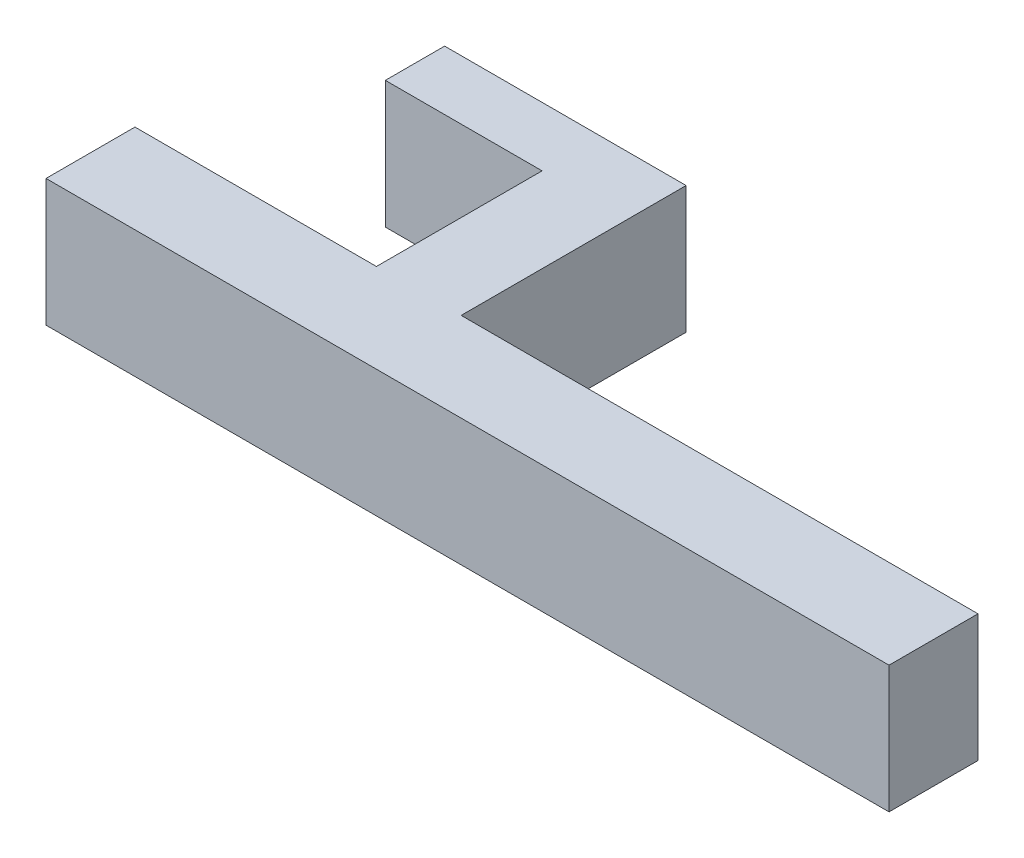
SolidWorks part; units mm, degrees
ref_plane "Plano frontal" through (0, 0, 0) normal (0, 0, 1) x (1, 0, 0)
ref_plane "Plano superior" through (0, 0, 0) normal (0, 1, 0) x (1, 0, 0)
ref_plane "Plano direito" through (0, 0, 0) normal (1, 0, 0) x (0, 0, -1)
sketch "Esboço1" plane through (0, 0, 0) normal (0, 1, 0) x (1, 0, 0)
  line L0 (0, 0) -> (19.9, 0)
  line L1 (19.9, 0) -> (19.9, 2.5)
  line L2 (19.9, 2.5) -> (7.7, 2.5)
  line L3 (7.7, 2.5) -> (7.7, 7.91)
  line L4 (7.7, 7.91) -> (2, 7.91)
  line L5 (2, 7.91) -> (2, 5.91)
  line L6 (2, 5.91) -> (5.7, 5.91)
  line L7 (5.7, 5.91) -> (5.7, 2.5)
  line L8 (5.7, 2.5) -> (0, 2.5)
  line L9 (0, 2.5) -> (0, 0)
  line L10 (2.1037, 2.5) -> (2.1037, 5.91) construction
  line L12 (2, 7.61) -> (7.7, 7.61)
  line L13 (2, 6.21) -> (5.7, 6.21)
  line L14 (5.7, 6.21) -> (5.7, 5.91)
  line L15 (5.7, 2.5) -> (5.7, 2.3)
  line L16 (5.7, 2.3) -> (0, 2.3)
  line L17 (7.7, 2.5) -> (7.7, 2.3)
  line L18 (7.7, 2.3) -> (19.9, 2.3)
  line L19 (19.9, 0.2) -> (0, 0.2)
  dimension "D1" = 2
  dimension "D2" = 2
  dimension "D3" = 3.7
  dimension "D4" = 2
  dimension "D5" = 3.41
  dimension "D6" = 19.9
  dimension "D7" = 2.5
  dimension "D8" = 0.3
  dimension "D9" = 0.3
  dimension "D10" = 0.2
  dimension "D11" = 0.2
extrude "Ressalto-extrusão1" add sketch "Esboço1" along normal blind 3 contours L19 L1 L18 L17 L3 L12 L5 L13 L14 L7 L15 L16 L9
